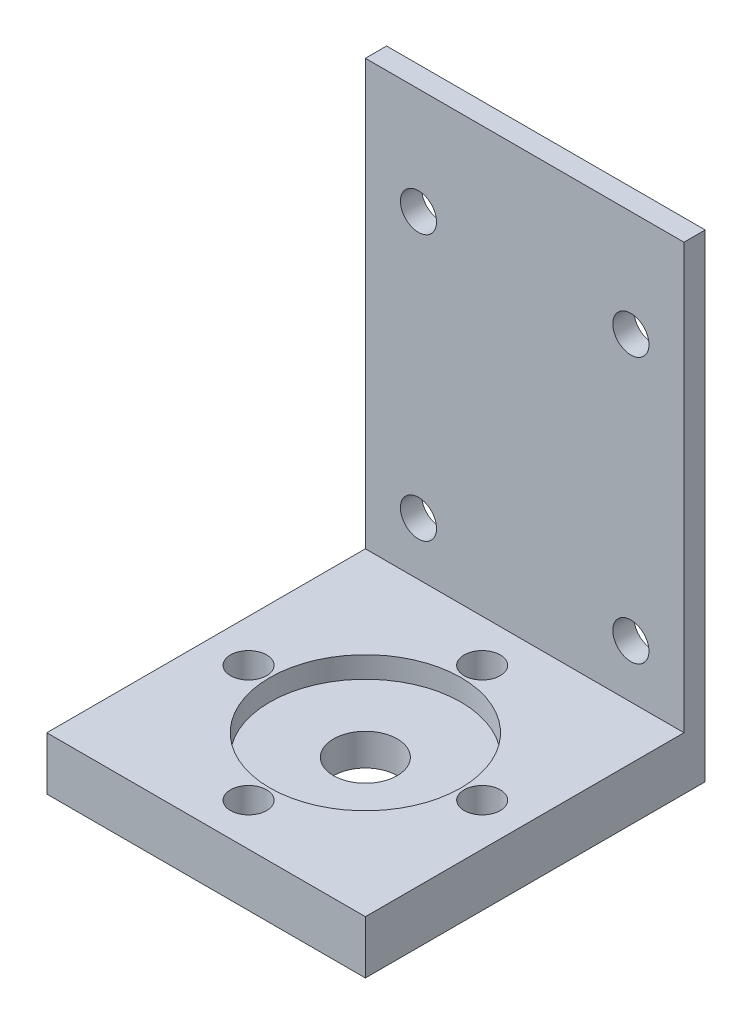
SolidWorks part; units mm, degrees
ref_plane "Front Plane" through (0, 0, 0) normal (0, 0, 1) x (1, 0, 0)
ref_plane "Top Plane" through (0, 0, 0) normal (0, 1, 0) x (1, 0, 0)
ref_plane "Right Plane" through (0, 0, 0) normal (1, 0, 0) x (0, 0, -1)
sketch "Sketch2" plane through (0, 0, 0) normal (1, 0, 0) x (0, 0, -1)
  line L0 (0, 0) -> (32, 0)
  line L1 (32, 0) -> (32, 45)
  line L2 (32, 45) -> (30, 45)
  line L3 (30, 45) -> (30, 5)
  line L4 (30, 5) -> (0, 5)
  line L5 (0, 5) -> (0, 0)
  dimension "D1" = 2
  dimension "D2" = 30
  dimension "D3" = 5
  dimension "D4" = 40
extrude "Boss-Extrude1" add sketch "Sketch2" along normal blind 30
sketch "Sketch3" plane through (0, 5, 0) normal (0, 1, 0) x (1, 0, 0)
  line L0 (0, 0) -> (30, 30) construction
  circle A0 centre (15, 15) radius 9
  circle A1 centre (15, 15) radius 3
  dimension "D1" = 18
  dimension "D2" = 6
extrude "Cut-Extrude1" cut sketch "Sketch3" against normal blind 2
sketch "Sketch7" plane through (0, 5, 0) normal (0, 1, 0) x (1, 0, 0)
  circle A0 centre (15, 15) radius 3
extrude "Cut-Extrude2" cut sketch "Sketch7" against normal through all
sketch "Sketch8" plane through (0, 3, 0) normal (0, 1, 0) x (1, 0, 0)
  line L0 (0, 15) -> (30, 15) construction
  line L1 (0, 30) -> (0, 0) construction
  line L2 (30, 30) -> (30, 0) construction
  line L3 (15, 30) -> (15, 0) construction
  line L4 (30, 30) -> (0, 30) construction
  line L5 (30, 0) -> (0, 0) construction
  circle A0 centre (4, 15) radius 1.7
  circle A1 centre (26, 15) radius 1.7
  circle A2 centre (15, 4) radius 1.7
  circle A3 centre (15, 26) radius 1.7
  circle A5 centre (15, 15) radius 11
  point P22 (26, 15)
  point P23 (15, 4)
  point P24 (15, 26)
  point P25 (4, 26.4934)
  point P26 (4, 15)
  point P27 (4, 23.4451)
  point P28 (4, 15)
  dimension "D1" = 3.4
  dimension "D5" = 22
extrude "Cut-Extrude3" cut sketch "Sketch8" against normal through all and the other way blind 2 contours A0 | A3 | A1 | A2
sketch "Sketch9" plane through (0, 0, -30) normal (0, 0, 1) x (1, 0, 0)
  line L0 (30, 0) -> (0, 0) construction
  line L1 (30, 45) -> (0, 45) construction
  line L2 (30, 45) -> (30, 5) construction
  circle A0 centre (5, 35) radius 1.7
  circle A1 centre (25, 35) radius 1.7
  circle A2 centre (25, 10) radius 1.7
  circle A3 centre (5, 10) radius 1.7
  point P11 (5, 38.3042)
  point P12 (26.2207, 38.3042)
  point P15 (25.4913, 35)
  point P16 (25.4913, 10)
  point P17 (0, 0)
  dimension "D1" = 3.4
  dimension "D2" = 5
  dimension "D6" = 3.4
  dimension "D3" = 10
  dimension "D4" = 10
  dimension "D5" = 25
  dimension "D7" = 10
  dimension "D8" = 10
  dimension "D9" = 25
  dimension "D10" = 5
extrude "Cut-Extrude4" cut sketch "Sketch9" against normal through all
equation "\"FT1 L\" = 30mm"
equation "\"FT1 H\" = 30mm"
equation "\"FT1 b\"= 5mm"
equation "\"FT2 H\"= 40mm"
equation "\"FT2 b\"= 2mm"
equation "\"Bolt holes\"= 3.4mm"
equation "\"FT1 Shaft hole\"= 6mm"
equation "\"FT1 Base hole\"= 18mm"
equation "\"D1@Sketch2\"=\"FT2 b\""
equation "\"D2@Sketch2\"=\"FT1 H\""
equation "\"D3@Sketch2\"=\"FT1 b\""
equation "\"D4@Sketch2\"=\"FT2 H\""
equation "\"D1@Boss-Extrude1\"=\"FT1 L\""
equation "\"D1@Sketch3\"=\"FT1 Base hole\""
equation "\"D2@Sketch3\"=\"FT1 Shaft hole\""
equation "\"D1@Sketch8\"=\"Bolt holes\""
